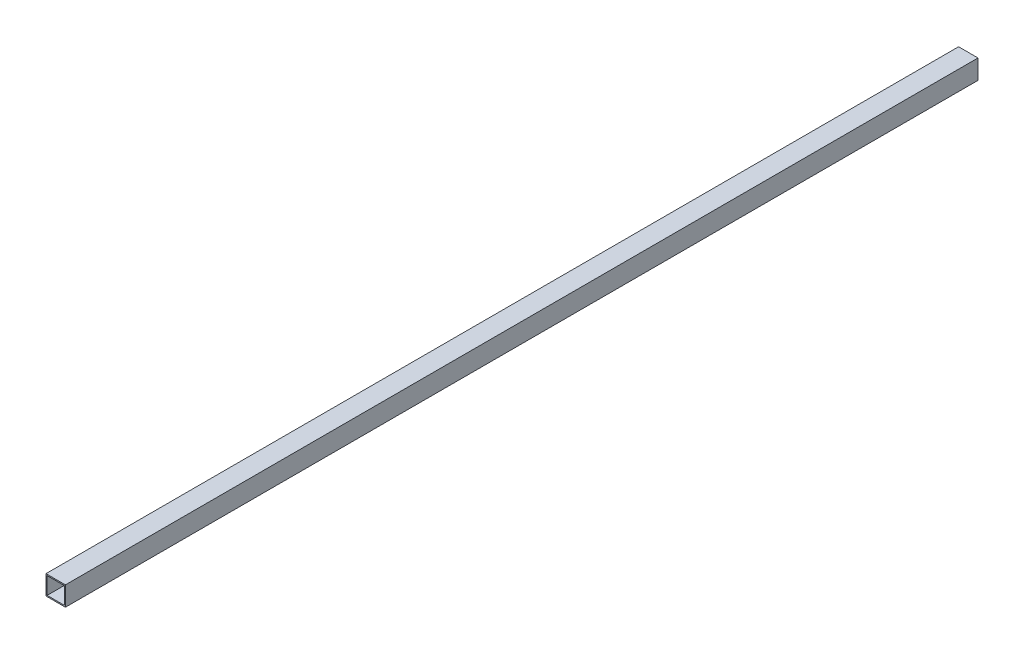
SolidWorks part; units mm, degrees
ref_plane "Front Plane" through (0, 0, 0) normal (0, 0, 1) x (1, 0, 0)
ref_plane "Top Plane" through (0, 0, 0) normal (0, 1, 0) x (1, 0, 0)
ref_plane "Right Plane" through (0, 0, 0) normal (1, 0, 0) x (0, 0, -1)
sketch "Sketch1" plane through (0, 0, 0) normal (0, 0, 1) x (1, 0, 0)
  line L1 (0, 0) -> (25.4, 0)
  line L2 (0, 0) -> (0, 25.4)
  line L3 (0, 25.4) -> (25.4, 25.4)
  line L4 (25.4, 0) -> (25.4, 25.4)
  dimension "D1" = 25.4
  dimension "D2" = 25.4
extrude "Extrude-Thin1" add sketch "Sketch1" along normal blind 1193.8 thin thin type one direction reverse wall 1.524
